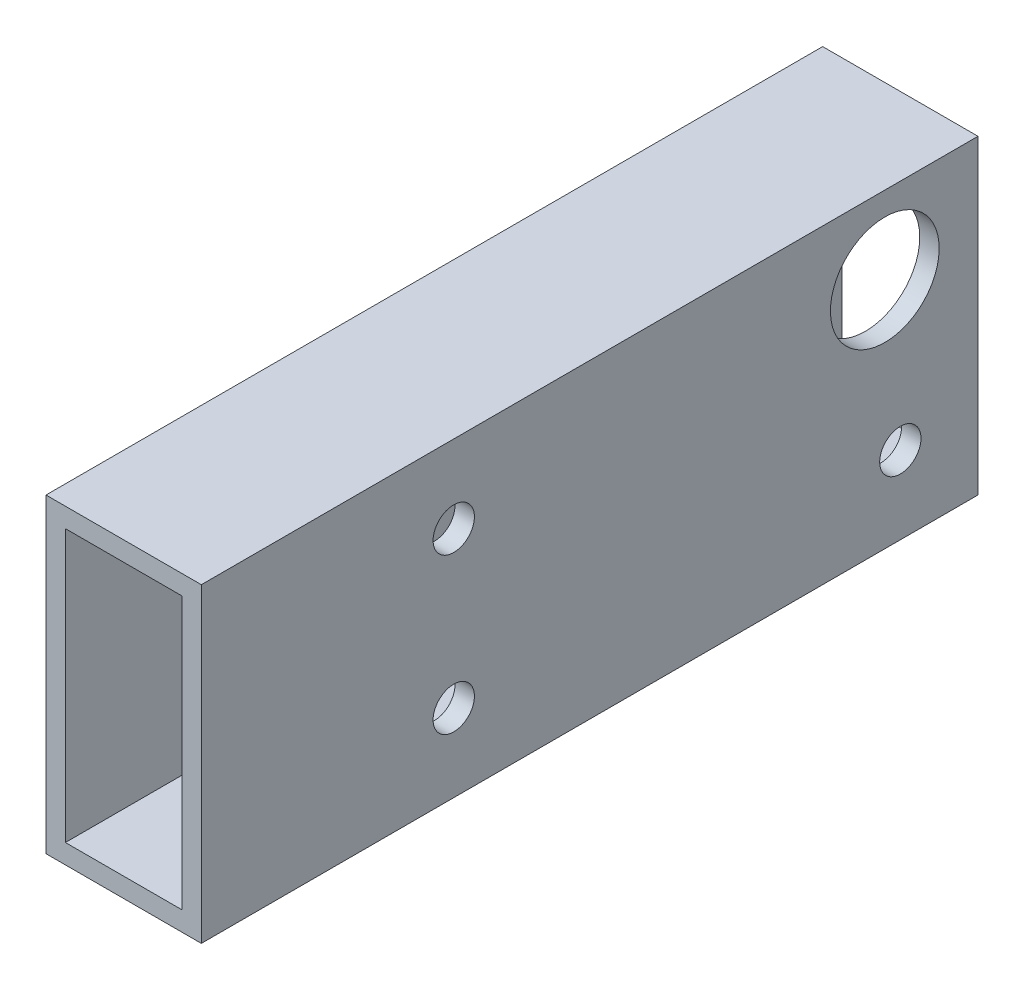
SolidWorks part; units mm, degrees
material "6061-T4 (SS)"
ref_plane "Front Plane" through (0, 0, 0) normal (0, 0, 1) x (1, 0, 0)
ref_plane "Top Plane" through (0, 0, 0) normal (0, 1, 0) x (1, 0, 0)
ref_plane "Right Plane" through (0, 0, 0) normal (1, 0, 0) x (0, 0, -1)
sketch "Sketch1" plane through (0, 0, 0) normal (0, 0, 1) x (1, 0, 0)
  line L0 (-9.525, 22.225) -> (9.525, 22.225)
  line L1 (-12.7, 25.4) -> (12.7, 25.4)
  line L2 (-12.7, 25.4) -> (-12.7, -25.4)
  line L3 (-12.7, -25.4) -> (12.7, -25.4)
  line L4 (12.7, 25.4) -> (12.7, -25.4)
  line L5 (-12.7, 25.4) -> (12.7, -25.4) construction
  line L6 (-12.7, -25.4) -> (12.7, 25.4) construction
  line L7 (9.525, 22.225) -> (9.525, -22.225)
  line L8 (-9.525, -22.225) -> (9.525, -22.225)
  line L9 (-9.525, 22.225) -> (-9.525, -22.225)
  point P0 (0, 0)
  dimension "D1" = 50.8
  dimension "D2" = 25.4
  dimension "D3" = 3.175
extrude "Boss-Extrude1" add sketch "Sketch1" along normal mid plane 127
sketch "Sketch2" plane through (12.7, 0, 0) normal (1, 0, 0) x (0, 0, -1)
  line L0 (63.5, -25.4) -> (63.5, 25.4) construction
  line L2 (63.5, 0) -> (-63.5, 0) construction
  line L3 (-63.5, -25.4) -> (-63.5, 25.4) construction
  line L4 (-22.225, -12.7) -> (-22.225, 12.7) construction
  line L5 (-22.225, 12.7) -> (63.5, 12.7) construction
  line L6 (-22.225, -12.7) -> (90.7078, -12.7) construction
  circle A1 centre (-22.225, 12.7) radius 3.3782
  circle A2 centre (-22.225, -12.7) radius 3.3782
  circle A3 centre (50.8, -12.7) radius 3.3782
  point P13 (-22.225, 0)
  dimension "D5" = 6.7564
  dimension "D3" = 25.4
  dimension "D4" = 85.725
  dimension "D6" = 12.7
extrude "Cut-Extrude3" cut sketch "Sketch2" against normal through all
sketch "Sketch3" plane through (12.7, 0, 0) normal (1, 0, 0) x (0, 0, -1)
  line L0 (63.5, -25.4) -> (63.5, 25.4) construction
  line L1 (-63.5, 25.4) -> (63.5, 25.4) construction
  circle A0 centre (48.26, 12.7) radius 8.89
  dimension "D1" = 17.78
  dimension "D2" = 15.24
  dimension "D3" = 12.7
extrude "Cut-Extrude4" cut sketch "Sketch3" against normal through all
